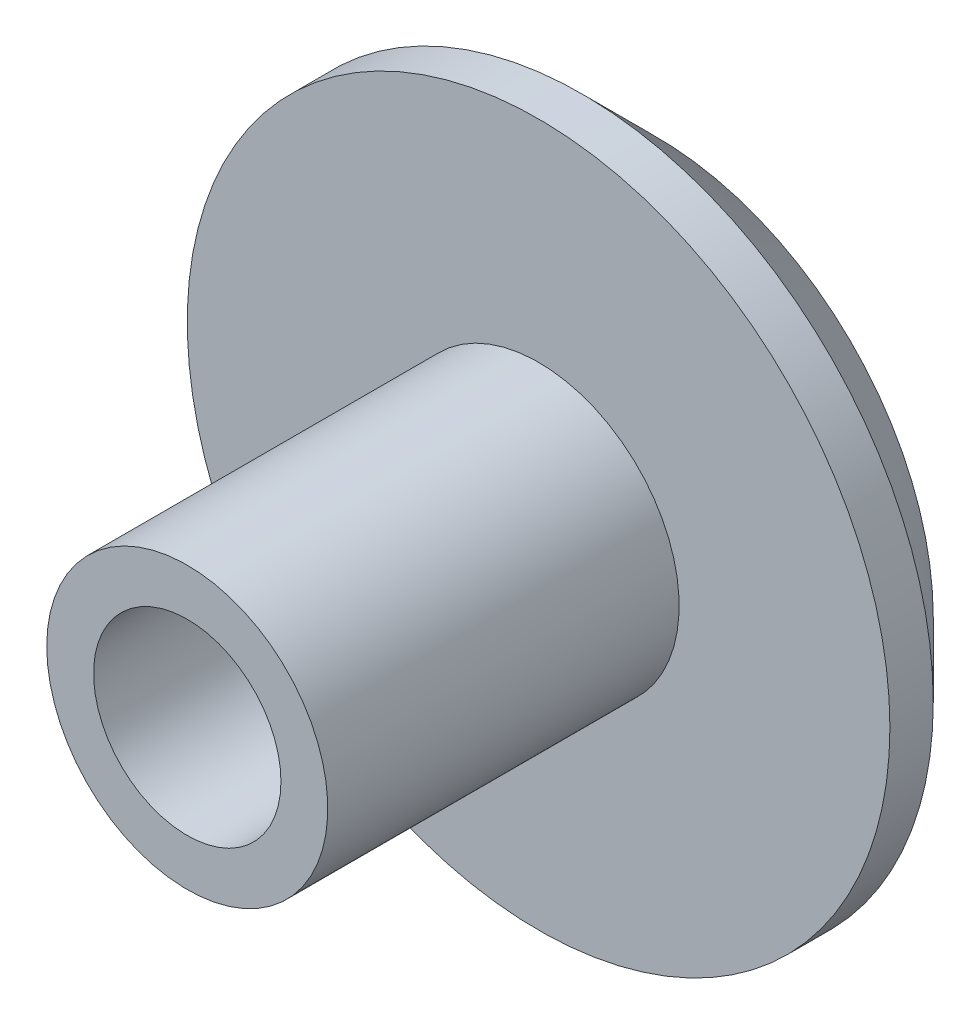
SolidWorks part; units mm, degrees
material "ABS"
ref_plane "Front Plane" through (0, 0, 0) normal (0, 0, 1) x (1, 0, 0)
ref_plane "Top Plane" through (0, 0, 0) normal (0, 1, 0) x (1, 0, 0)
ref_plane "Right Plane" through (0, 0, 0) normal (1, 0, 0) x (0, 0, -1)
sketch "Sketch1" plane through (0, 0, 0) normal (0, 0, 1) x (1, 0, 0)
  circle A0 centre (0, 0) radius 4.7625
extrude "Boss-Extrude1" add sketch "Sketch1" along normal blind 1.5875
sketch "Sketch3" plane through (0, 0, 1.5875) normal (0, 0, 1) x (1, 0, 0)
  circle A0 centre (0, 0) radius 1.905
  dimension "D1" = 3.81
extrude "Boss-Extrude2" add sketch "Sketch3" along normal blind 4.7625
sketch "Sketch4" plane through (0, 0, 6.35) normal (0, 0, 1) x (1, 0, 0)
  circle A0 centre (0, 0) radius 1.27
extrude "Cut-Extrude1" cut sketch "Sketch4" against normal through all
chamfer "Chamfer2" distance 1 angle 45 1 edges at (4.7625, 0, 0)
